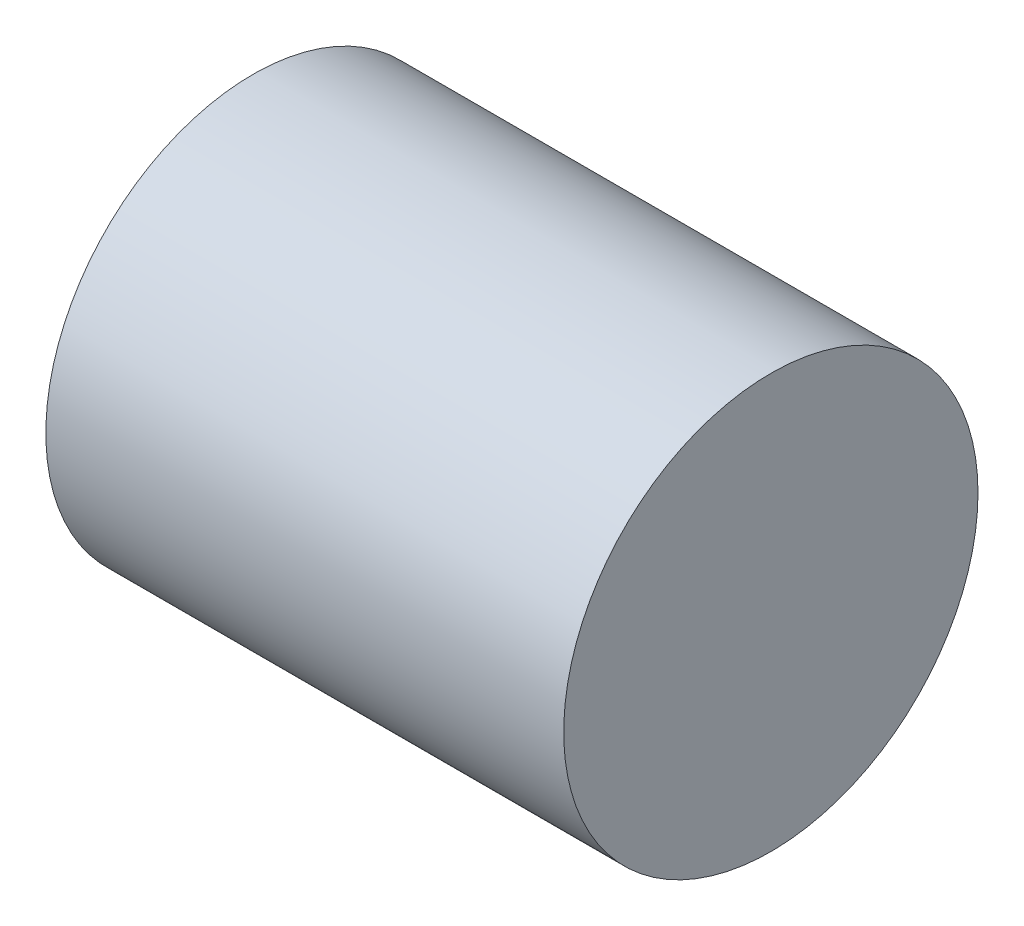
SolidWorks part; units mm, degrees
ref_plane "Front Plane" through (0, 0, 0) normal (0, 0, 1) x (1, 0, 0)
ref_plane "Top Plane" through (0, 0, 0) normal (0, 1, 0) x (1, 0, 0)
ref_plane "Right Plane" through (0, 0, 0) normal (1, 0, 0) x (0, 0, -1)
sketch "Sketch1" plane through (0, 0, 0) normal (1, 0, 0) x (0, 0, -1)
  circle A0 centre (0, 0) radius 4
  dimension "D1" = 8
extrude "Boss-Extrude1" add sketch "Sketch1" along normal blind 10
sketch "Sketch2" plane through (0, 0, 0) normal (-1, 0, 0) x (0, 0, 1)
  circle A0 centre (0, 0) radius 1.5
  dimension "D1" = 3
extrude "Cut-Extrude1" cut sketch "Sketch2" against normal blind 5
